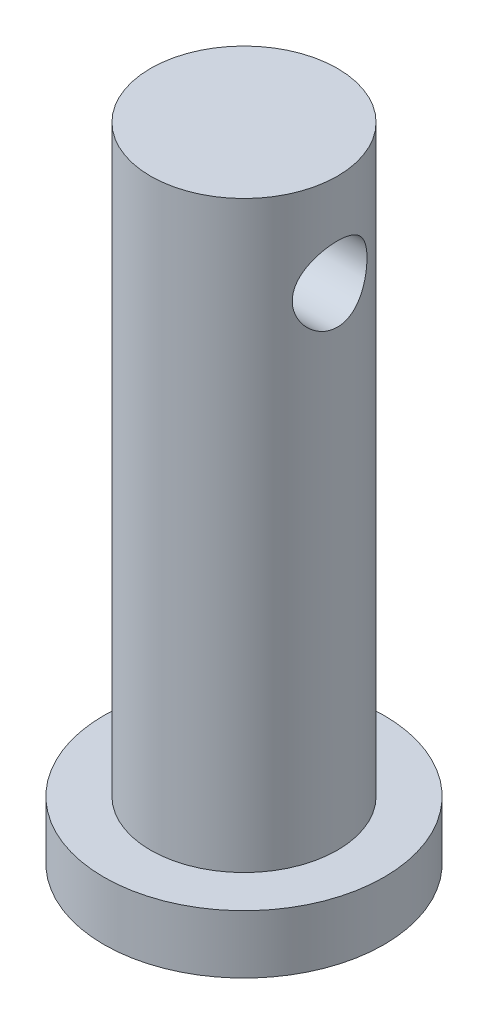
SolidWorks part; units mm, degrees
ref_plane "前视基准面" through (0, 0, 0) normal (0, 0, 1) x (1, 0, 0)
ref_plane "上视基准面" through (0, 0, 0) normal (0, 1, 0) x (1, 0, 0)
ref_plane "右视基准面" through (0, 0, 0) normal (1, 0, 0) x (0, 0, -1)
sketch "草图1" plane through (0, 0, 0) normal (0, 1, 0) x (1, 0, 0)
  circle A0 centre (0, 0) radius 6
  dimension "D1" = 12
extrude "凸台-拉伸1" add sketch "草图1" along normal blind 2.5
sketch "草图2" plane through (0, 2.5, 0) normal (0, 1, 0) x (1, 0, 0)
  circle A0 centre (0, 0) radius 4
  dimension "D1" = 8
extrude "凸台-拉伸2" add sketch "草图2" along normal blind 25
sketch "草图3" plane through (0, 0, 0) normal (1, 0, 0) x (0, 0, -1)
  line L0 (4, 27.5) -> (-4, 27.5) construction
  circle A0 centre (0, 23.5) radius 1.6
  point P4 (0, 0)
  dimension "D1" = 3.2
  dimension "D2" = 4
extrude "切除-拉伸1" cut sketch "草图3" against normal through all both and the other way through all
